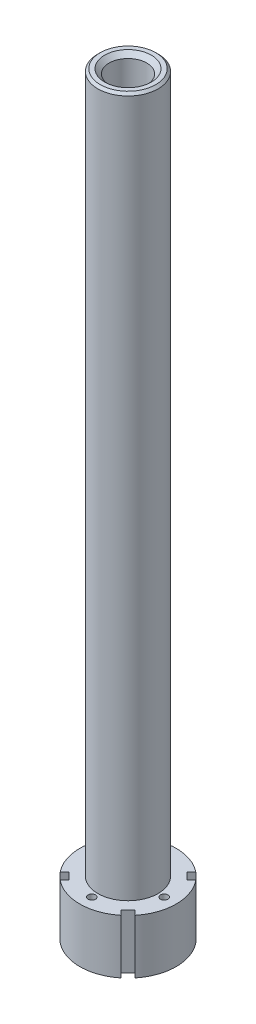
SolidWorks part; units mm, degrees
ref_plane "前视基准面" through (0, 0, 0) normal (0, 0, 1) x (1, 0, 0)
ref_plane "上视基准面" through (0, 0, 0) normal (0, 1, 0) x (1, 0, 0)
ref_plane "右视基准面" through (0, 0, 0) normal (1, 0, 0) x (0, 0, -1)
sketch "草图1" plane through (0, 0, 0) normal (0, 1, 0) x (1, 0, 0)
  circle A0 centre (0, 0) radius 10
  dimension "D1" = 20
extrude "凸台-拉伸1" add sketch "草图1" along normal blind 250
sketch "草图6" plane through (0, 0, 0) normal (0, -1, 0) x (1, 0, 0)
  circle A0 centre (0, 0) radius 16
  dimension "D1" = 32
extrude "凸台-拉伸2" add sketch "草图6" against normal blind 18
sketch "草图2" plane through (0, 250, 0) normal (0, -1, 0) x (1, 0, 0)
  circle A0 centre (0, 0) radius 6
  dimension "D1" = 12
extrude "切除-拉伸1" cut sketch "草图2" along normal blind 260 from offset 30
hole_wizard "M14x1.5 螺纹孔1" positions "草图3" profile "草图5" tap size "M14x1.5" standard "GB"
sketch "草图3" plane through (0, 250, 0) normal (0, 1, 0) x (1, 0, 0)
  point P0 (0, 0)
cosmetic thread "孔螺蚊线1" parameters "D1"=30, "D2"=14
sketch "草图5" plane through (0, 250, 0) normal (1, 0, 0) x (0, 0, 1)
  line L0 (0, 0) -> (0, 38.7554)
  line L1 (0, 38.7554) -> (6.25, 35)
  line L2 (6.25, 35) -> (6.25, 0)
  line L5 (6.25, 0) -> (0, 0)
  line L10 (0, 38.7554) -> (-6.25, 35) construction
  line L11 (0, -6.35) -> (0, 107.95) construction
  dimension "螺纹孔钻头直径" = 12.5
  dimension "螺纹孔钻头深度" = 35
  dimension "导头角度" = 118
chamfer "倒角1" distance 1.5 angle 45 1 edges at (0, 250, 6.25)
sketch "草图8" plane through (0, 0, 0) normal (0, -1, 0) x (1, 0, 0)
  circle A0 centre (0, 0) radius 8
  dimension "D1" = 16
extrude "切除-拉伸2" cut sketch "草图8" against normal blind 15.5
sketch "草图9" plane through (0, 0, 0) normal (0, -1, 0) x (-1, 0, 0)
  circle A0 centre (0, 0) radius 12
  dimension "D1" = 24
hole_wizard "M3 螺纹孔1" positions "草图10" profile "草图11" tap size "M3" standard "GB"
sketch "草图10" plane through (0, 0, 0) normal (0, -1, 0) x (-1, 0, 0)
  circle A0 centre (0, 0) radius 12 construction
  point P0 (0, 12)
  point P4 (12, 0)
  point P6 (0, -12)
  point P8 (-12, 0)
sketch "草图11" plane through (0, 0, -12) normal (1, 0, 0) x (0, 0, -1)
  line L0 (0, 0) -> (0, 25.7511)
  line L1 (0, 25.7511) -> (1.25, 25)
  line L2 (1.25, 25) -> (1.25, 0)
  line L5 (1.25, 0) -> (0, 0)
  line L10 (0, 25.7511) -> (-1.25, 25) construction
  line L11 (0, -6.35) -> (0, 107.95) construction
  dimension "螺纹孔钻头直径" = 2.5
  dimension "螺纹孔钻头深度" = 25
  dimension "导头角度" = 118
cosmetic thread "孔螺蚊线2" parameters "D1"=13, "D2"=3
cosmetic thread "孔螺蚊线3" parameters "D1"=13, "D2"=3
cosmetic thread "孔螺蚊线4" parameters "D1"=13, "D2"=3
cosmetic thread "孔螺蚊线5" parameters "D1"=13, "D2"=3
sketch "草图13" plane through (0, 0, 0) normal (0, -1, 0) x (1, 0, 0)
  line L0 (-9.7581, 9.7581) -> (-11.3137, 11.3137)
  line L1 (0, 0) -> (0, 9.0094) construction
  circle A0 centre (0, 0) radius 16 construction
  circle A1 centre (0, 0) radius 13.8 construction
  dimension "D1" = 2.2
  dimension "D2" = 45
extrude "切除-拉伸-薄壁1" cut sketch "草图13" against normal through all and the other way through all thin thin type mid plane wall 3.2
pattern_circular "阵列(圆周)1" count 4 over 360 about axis through (0, 0, 0) along (0, 1, 0) of "切除-拉伸-薄壁1"
chamfer "倒角2" distance 0.8 angle 45 1 edges at (0, 250, 10)
